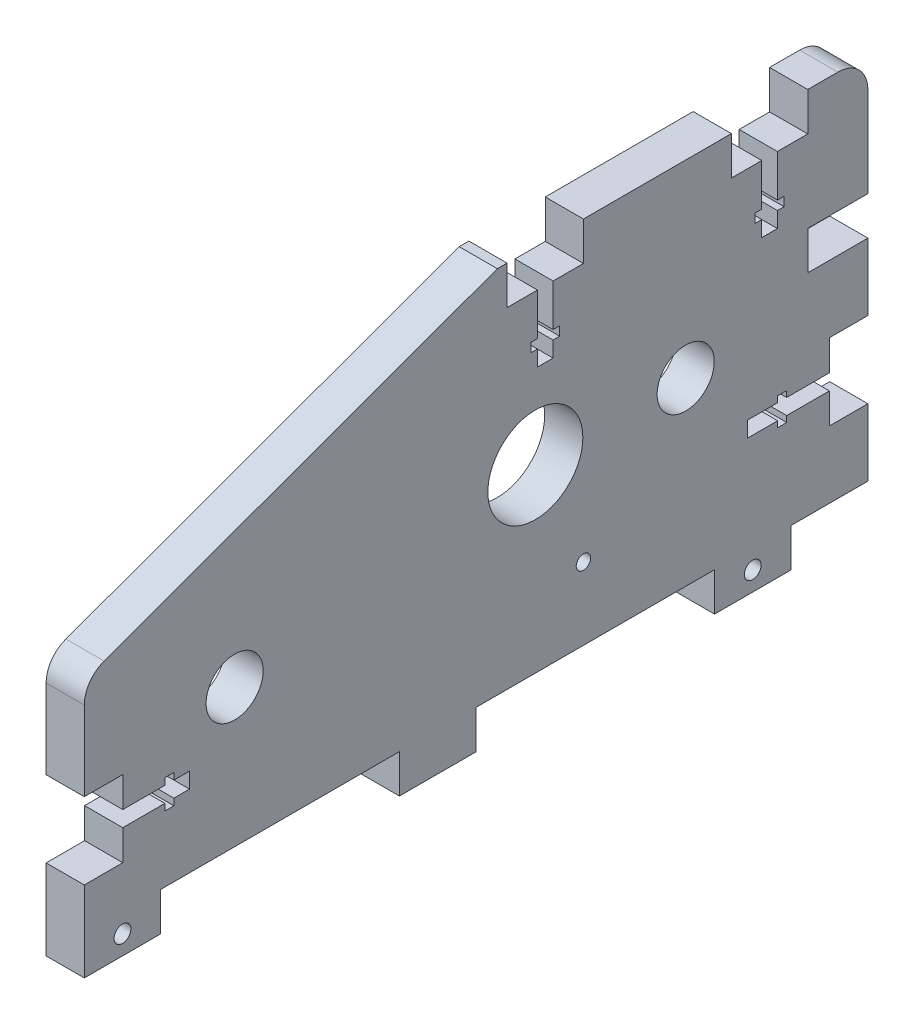
SolidWorks part; units mm, degrees
material "Acrylic (Medium-high impact)"
ref_plane "Front Plane" through (0, 0, 0) normal (0, 0, 1) x (1, 0, 0)
ref_plane "Top Plane" through (0, 0, 0) normal (0, 1, 0) x (1, 0, 0)
ref_plane "Right Plane" through (0, 0, 0) normal (1, 0, 0) x (0, 0, -1)
sketch "Sketch2" plane through (0, 0, 0) normal (1, 0, 0) x (0, 0, -1)
  line L0 (65.15, -30.7) -> (65.15, 30.7)
  line L1 (65.15, 30.7) -> (-65.15, 30.7)
  line L2 (-65.15, 30.7) -> (-65.15, -30.7)
  line L3 (-65.15, -30.7) -> (-65.15, -37.1)
  line L4 (-65.15, -37.1) -> (-52.45, -37.1)
  line L5 (-52.45, -37.1) -> (-52.45, -30.7)
  line L6 (-52.45, -30.7) -> (-12.75, -30.7)
  line L7 (-12.75, -30.7) -> (-12.75, -37.1)
  line L8 (-12.75, -37.1) -> (-0.05, -37.1)
  line L9 (-0.05, -37.1) -> (-0.05, -30.7)
  line L10 (-0.05, -30.7) -> (39.65, -30.7)
  line L11 (39.65, -30.7) -> (39.65, -37.1)
  line L12 (39.65, -37.1) -> (52.35, -37.1)
  line L13 (52.35, -37.1) -> (52.35, -30.7)
  line L14 (52.35, -30.7) -> (65.15, -30.7)
  line L15 (58.75, -6.85) -> (58.75, 4.3) construction
  line L16 (65.15, -19.55) -> (58.75, -19.55)
  line L17 (65.15, -19.55) -> (65.15, -6.85)
  line L18 (65.15, -6.85) -> (58.75, -6.85)
  line L19 (58.75, -19.55) -> (58.75, -6.85)
  line L20 (65.15, 4.3) -> (55.15, 4.3)
  line L21 (65.15, 4.3) -> (65.15, 10.7)
  line L22 (65.15, 10.7) -> (55.15, 10.7)
  line L23 (55.15, 4.3) -> (55.15, 10.7)
  line L24 (58.75, -19.55) -> (58.75, -30.7) construction
  line L26 (50.15, -10.9) -> (51.65, -10.9)
  line L27 (50.15, -10.9) -> (50.15, -15.5)
  line L28 (50.15, -15.5) -> (51.65, -15.5)
  line L29 (51.65, -10.9) -> (51.65, -15.5)
  line L30 (45.15, -11.9) -> (65.15, -11.9)
  line L31 (45.15, -11.9) -> (45.15, -14.5)
  line L32 (45.15, -14.5) -> (65.15, -14.5)
  line L33 (65.15, -11.9) -> (65.15, -14.5)
  circle A0 centre (-58.8, -33.9) radius 1.4
  circle A2 centre (46, -33.9) radius 1.4
  point P21 (-65.15, -33.9)
  point P22 (-58.8, -37.1)
  point P24 (46, -37.1)
  point P36 (58.75, -13.2)
  point P37 (51.65, -13.2)
  point P38 (0, 30.7)
  point P39 (-65.15, 0)
  point P52 (45.15, -13.2)
  dimension "D5" = 2.8
  dimension "D1" = 6.4
  dimension "D2" = 12.7
  dimension "D3" = 117.5
  dimension "D4" = 12.8
  dimension "D7" = 35
  dimension "D8" = 1.5
  dimension "D9" = 4.6
  dimension "D11" = 10
  dimension "D12" = 15
  dimension "D15" = 20
  dimension "D19" = 2.6
  dimension "D20" = 20
extrude "Boss-Extrude1" add sketch "Sketch2" along normal blind 6.35 contours L20 L23 L22 L0 L1 L2 L3 L4 L5 L6 L7 L8 L9 L10 L11 L12 L13 L14 L16 L19 L18 A2 A0 L26 L29 L28 L27
sketch "Sketch3" plane through (6.35, 0, 0) normal (1, 0, 0) x (0, 0, -1)
  line L3 (-65.15, 30.7) -> (-65.15, -37.1) construction
  line L5 (-52.45, -30.7) -> (-12.75, -30.7) construction
  circle A0 centre (-40.15, -7.7) radius 4.75
  circle A1 centre (34.85, -0.7) radius 4.75
  circle A2 centre (9.85, -0.7) radius 7.9
  dimension "D1" = 15.8
  dimension "D2" = 9.5
  dimension "D3" = 25
  dimension "D4" = 75
  dimension "D5" = 7
  dimension "D6" = 100
  dimension "D7" = 23
extrude "Axii" cut sketch "Sketch3" against normal through all
chamfer "Chamfer1" distance 25 angle 70 1 edges at (3.175, 30.7, 65.15)
fillet "Fillet1" radius 5 2 edges at (3.175, 30.7, -65.15) (3.175, 5.7, 65.15)
sketch "Sketch4" plane through (6.35, 0, 0) normal (1, 0, 0) x (0, 0, -1)
  circle A0 centre (34.85, 14.3) radius 1.4
  circle A1 centre (34.85, -12.7) radius 1.4
  circle A2 centre (-13.15, -16.7) radius 1.4
  circle A3 centre (-25.15, -16.7) radius 1.4
  circle A4 centre (9.85, -0.7) radius 7.9 construction
  dimension "D1" = 2.8
  dimension "D2" = 12
  dimension "D3" = 15
  dimension "D4" = 25
  dimension "D5" = 16
  dimension "D6" = 35
  dimension "D7" = 12
extrude "MotorHoles" [suppressed] cut sketch "Sketch4" against normal through all
sketch "Sketch5" plane through (6.35, 0, 0) normal (1, 0, 0) x (0, 0, -1)
  line L0 (60.15, 30.7) -> (3.5369, 30.7) construction
  line L1 (55.15, 30.7) -> (42.45, 30.7)
  line L2 (55.15, 30.7) -> (55.15, 24.3)
  line L3 (55.15, 24.3) -> (42.45, 24.3)
  line L4 (42.45, 30.7) -> (42.45, 24.3)
  line L5 (5.15, 30.7) -> (17.85, 30.7)
  line L6 (5.15, 30.7) -> (5.15, 24.3)
  line L7 (5.15, 24.3) -> (17.85, 24.3)
  line L8 (17.85, 30.7) -> (17.85, 24.3)
  line L9 (-12.75, -37.1) -> (-0.05, -37.1) construction
  line L10 (-12.75, -30.7) -> (-12.75, -37.1) construction
  line L11 (-65.15, 2.199) -> (-65.15, -37.1) construction
  line L12 (10.2, 24.3) -> (12.8, 24.3)
  line L13 (10.2, 24.3) -> (10.2, 13.2)
  line L14 (10.2, 13.2) -> (12.8, 13.2)
  line L15 (12.8, 24.3) -> (12.8, 13.2)
  line L16 (45.15, -11.9) -> (45.15, -14.5) construction
  line L17 (47.5, 24.3) -> (50.1, 24.3)
  line L18 (47.5, 24.3) -> (47.5, 13.2)
  line L19 (47.5, 13.2) -> (50.1, 13.2)
  line L20 (50.1, 24.3) -> (50.1, 13.2)
  line L21 (9.1, 17.3) -> (13.9, 17.3)
  line L22 (9.1, 17.3) -> (9.1, 15.8)
  line L23 (9.1, 15.8) -> (13.9, 15.8)
  line L24 (13.9, 17.3) -> (13.9, 15.8)
  line L25 (46.4, 17.3) -> (51.2, 17.3)
  line L26 (46.4, 17.3) -> (46.4, 15.8)
  line L27 (46.4, 15.8) -> (51.2, 15.8)
  line L28 (51.2, 17.3) -> (51.2, 15.8)
  line L29 (50.15, -10.9) -> (51.65, -10.9) construction
  line L30 (65.15, 10.7) -> (65.15, 25.7) construction
  line L31 (-65.15, -11) -> (-58.75, -11)
  line L32 (-65.15, -11) -> (-65.15, -23.7)
  line L33 (-65.15, -23.7) -> (-58.75, -23.7)
  line L34 (-58.75, -11) -> (-58.75, -23.7)
  line L35 (-52.45, -30.7) -> (-12.75, -30.7) construction
  line L36 (-58.75, -16.05) -> (-47.65, -16.05)
  line L37 (-58.75, -16.05) -> (-58.75, -18.65)
  line L38 (-58.75, -18.65) -> (-47.65, -18.65)
  line L39 (-47.65, -16.05) -> (-47.65, -18.65)
  line L40 (-51.75, -14.95) -> (-50.25, -14.95)
  line L41 (-51.75, -14.95) -> (-51.75, -19.75)
  line L42 (-51.75, -19.75) -> (-50.25, -19.75)
  line L43 (-50.25, -14.95) -> (-50.25, -19.75)
  point P25 (11.5, 24.3)
  point P33 (48.8, 24.3)
  point P34 (48.8, 17.3)
  point P37 (11.5, 17.3)
  point P38 (48.8, 13.2)
  point P55 (-50.25, -17.35)
  point P56 (-47.65, -17.35)
  point P57 (-58.75, -17.35)
  dimension "D1" = 50
  dimension "D2" = 17.5
  dimension "D3" = 4.8
  dimension "D4" = 7
  dimension "D5" = 10
  dimension "D6" = 7
  dimension "D7" = 7
extrude "PlateAttachments" cut sketch "Sketch5" against normal through all
sketch "Sketch6" plane through (6.35, 0, 0) normal (1, 0, 0) x (0, 0, -1)
  line L0 (-65.15, -23.7) -> (-65.15, -37.1) construction
  line L1 (-0.05, -30.7) -> (39.65, -30.7) construction
  circle A0 centre (17.85, -18.7) radius 1.2
  dimension "D3" = 2.4
  dimension "D1" = 83
  dimension "D2" = 12
extrude "WireGuide" cut sketch "Sketch6" against normal through all
sketch "Sketch7" [suppressed] plane through (0, 0, 0) normal (-1, 0, 0) x (0, 0, 1)
  line L0 (-34.25, -30.7) -> (-23.75, -30.7)
  line L1 (-34.25, -30.7) -> (-34.25, -19.2)
  line L2 (-23.75, -30.7) -> (-23.75, -19.2)
  line L3 (-34.25, -19.2) -> (-23.75, -19.2)
  line L4 (0.05, -30.7) -> (-39.65, -30.7) construction
  line L5 (-65.15, -30.7) -> (-65.15, -19.55) construction
  dimension "D1" = 30.9
  dimension "D2" = 10
  dimension "D3" = 10.5
extrude "LimitSwitchHole" [suppressed] cut sketch "Sketch7" against normal through all
sketch "Sketch8" [suppressed] plane through (6.35, 0, 0) normal (1, 0, 0) x (0, 0, -1)
  line L0 (-52.45, -30.7) -> (-12.75, -30.7) construction
  line L1 (-22.35, -30.7) -> (-15.95, -30.7)
  line L2 (-22.35, -30.7) -> (-22.35, -24.3)
  line L3 (-22.35, -24.3) -> (-15.95, -24.3)
  line L4 (-15.95, -30.7) -> (-15.95, -24.3)
  line L5 (-25.15, -16.7) -> (-13.15, -16.7) construction
  line L7 (-50.35, -23.3) -> (-25.35, -23.3)
  line L8 (-50.35, -23.3) -> (-50.35, -25.3)
  line L9 (-50.35, -25.3) -> (-25.35, -25.3)
  line L10 (-25.35, -23.3) -> (-25.35, -25.3)
  line L11 (-50.35, -23.3) -> (-25.35, -25.3) construction
  line L12 (-50.35, -25.3) -> (-25.35, -23.3) construction
  point P6 (-19.15, -24.3)
  point P11 (-19.15, -16.7)
  point P12 (-37.85, -24.3)
  dimension "D2" = 25
  dimension "D1" = 6.4
  dimension "D3" = 3
  dimension "D4" = 2
extrude "Cut-Extrude2" [suppressed] cut sketch "Sketch8" against normal through all
